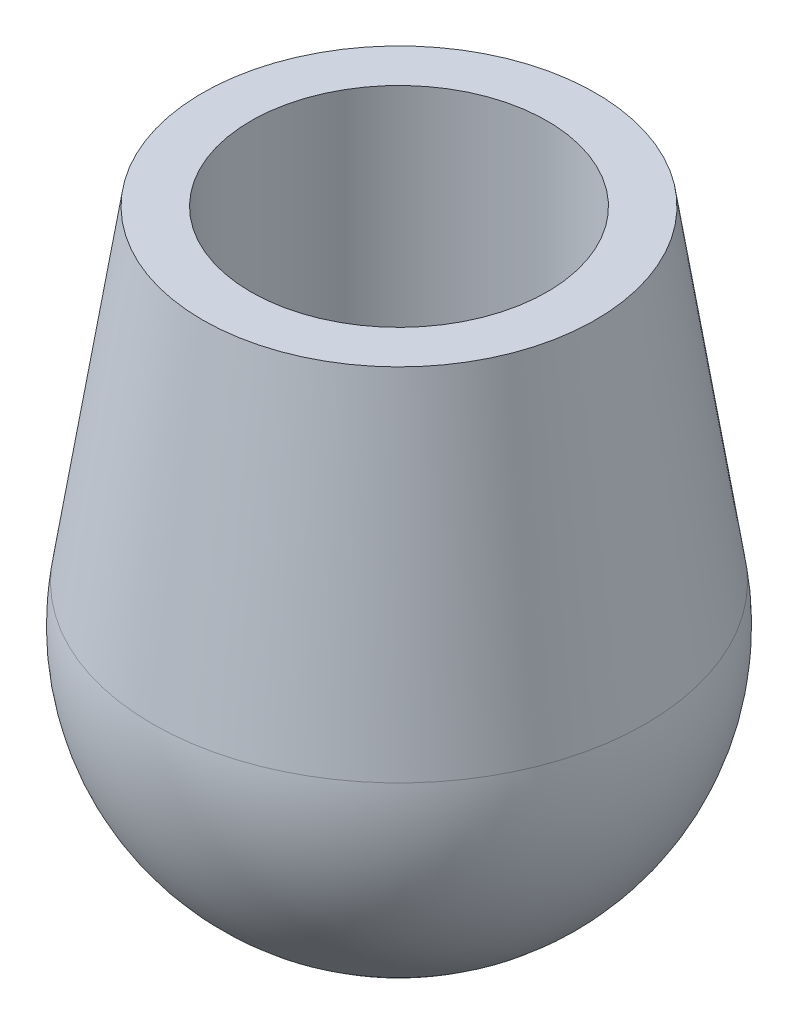
SolidWorks part; units mm, degrees
ref_plane "Front" through (0, 0, 0) normal (0, 0, 1) x (1, 0, 0)
ref_plane "Top" through (0, 0, 0) normal (0, 1, 0) x (1, 0, 0)
ref_plane "Right" through (0, 0, 0) normal (1, 0, 0) x (0, 0, -1)
sketch "Esquisse1" plane through (0, 0, 0) normal (0, 0, 1) x (1, 0, 0)
  line L0 (0, 0) -> (7.65, 0)
  line L1 (7.65, 0) -> (7.65, 25)
  line L2 (7.65, 25) -> (10.15, 25)
  line L3 (10.15, 25) -> (12.7269, 8.2184)
  line L4 (0, 6.2641) -> (0, -6.612) construction
  line L5 (7.65, 0) -> (9.7713, -2.1213) construction
  line L6 (0, 0) -> (0, -6.612)
  arc A0 (12.7269, 8.2184) -> (0, -6.612) centre (0, 6.2641) cw
  dimension "D1" = 15.3
  dimension "D2" = 2.5
  dimension "D3" = 3
  dimension "D4" = 135
  dimension "D5" = 25
revolve "Révolution1" add sketch "Esquisse1" angle 360 about L6
